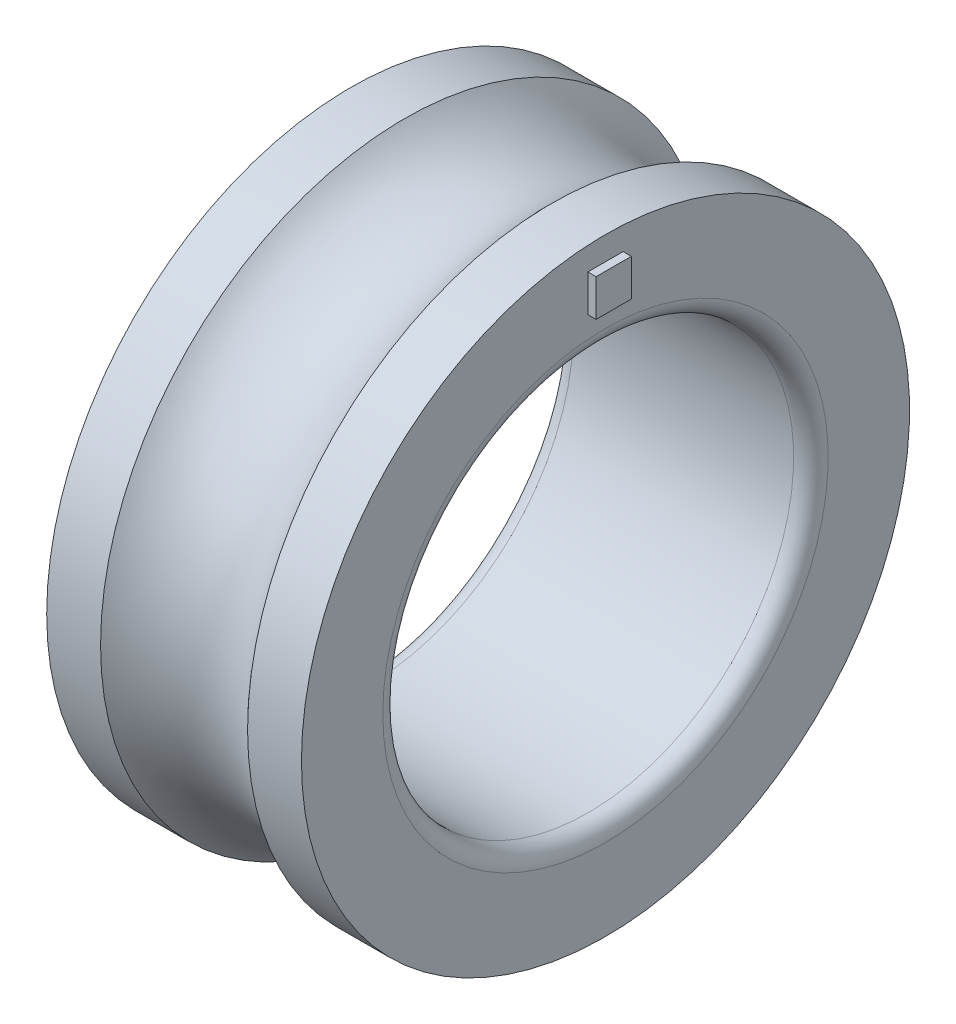
SolidWorks part; units mm, degrees
ref_plane "Front Plane" through (0, 0, 0) normal (0, 0, 1) x (1, 0, 0)
ref_plane "Top Plane" through (0, 0, 0) normal (0, 1, 0) x (1, 0, 0)
ref_plane "Right Plane" through (0, 0, 0) normal (1, 0, 0) x (0, 0, -1)
sketch "Sketch1" plane through (0, 0, 0) normal (0, 0, 1) x (1, 0, 0)
  line L0 (-15.1464, 0) -> (27.6407, 0) construction
  line L1 (0, 25) -> (0, 0) construction
  line L2 (-15.5, 37) -> (-8.9443, 37)
  line L3 (-15.5, 37) -> (-15.5, 27.1)
  line L4 (-13.4, 25) -> (13.4, 25)
  line L5 (15.5, 37) -> (15.5, 27.1)
  line L6 (-15.5, 37) -> (15.5, 25) construction
  line L7 (-15.5, 25) -> (15.5, 37) construction
  line L8 (8.9443, 37) -> (15.5, 37)
  arc A0 (-8.9443, 37) -> (8.9443, 37) centre (0, 45) ccw
  arc A1 (13.4, 25) -> (15.5, 27.1) centre (13.4, 27.1) ccw
  arc A2 (-15.5, 27.1) -> (-13.4, 25) centre (-13.4, 27.1) ccw
  point P3 (0, 31)
  dimension "D5" = 12
  dimension "D6" = 2.1
  dimension "D1" = 31
  dimension "D2" = 25
  dimension "D3" = 37
  dimension "D4" = 8
revolve "Revolve2" add sketch "Sketch1" angle 360 about L0
sketch "Sketch2" plane through (15.5, 0, 0) normal (1, 0, 0) x (0, 0, -1)
  line L1 (-2.1447, 29.6197) -> (2.1447, 29.6197)
  line L2 (-2.1447, 29.6197) -> (-2.1447, 34.1235)
  line L3 (-2.1447, 34.1235) -> (2.1447, 34.1235)
  line L4 (2.1447, 29.6197) -> (2.1447, 34.1235)
  line L5 (-2.1447, 29.6197) -> (2.1447, 34.1235) construction
  line L6 (-2.1447, 34.1235) -> (2.1447, 29.6197) construction
  point P0 (0, 31.8716)
extrude "Boss-Extrude1" add sketch "Sketch2" along normal blind 1
